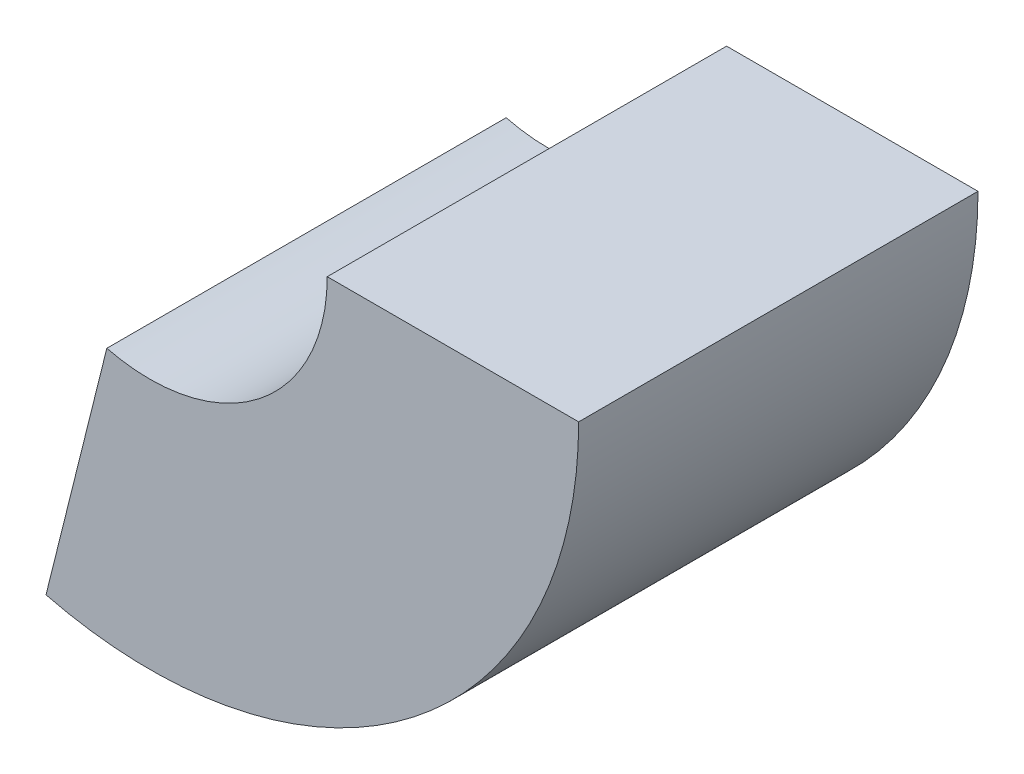
SolidWorks part; units mm, degrees
ref_plane "Front Plane" through (0, 0, 0) normal (0, 0, 1) x (1, 0, 0)
ref_plane "Top Plane" through (0, 0, 0) normal (0, 1, 0) x (1, 0, 0)
ref_plane "Right Plane" through (0, 0, 0) normal (1, 0, 0) x (0, 0, -1)
sketch "RevolveSketch" plane through (0, 0, 0) normal (0, 1, 0) x (1, 0, 0)
  line L1 (16, -11) -> (33, -11)
  line L2 (16, -11) -> (16, 16)
  line L3 (16, 16) -> (33, 16)
  line L4 (33, -11) -> (33, 16)
  line L5 (4, -16) -> (4, 23) construction
revolve "OrdinaryBossRevolve" add sketch "RevolveSketch" angle 104 about L5
